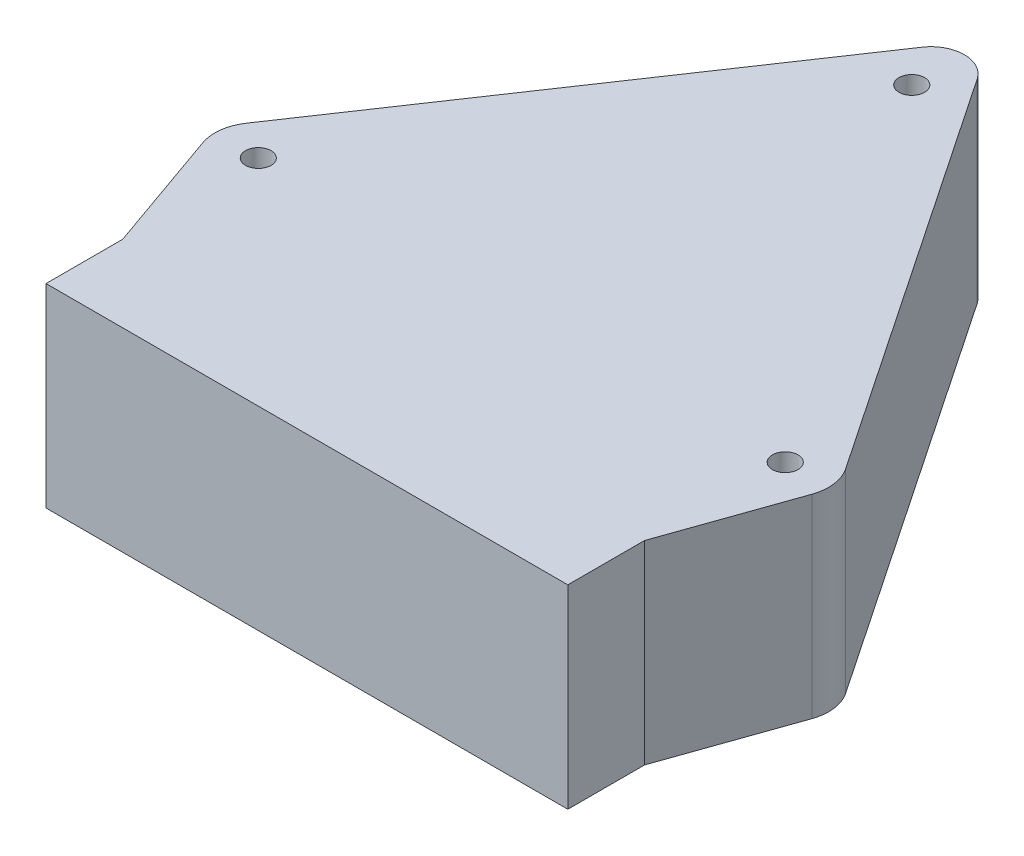
SolidWorks part; units mm, degrees
ref_plane "Front Plane" through (0, 0, 0) normal (0, 0, 1) x (1, 0, 0)
ref_plane "Top Plane" through (0, 0, 0) normal (0, 1, 0) x (1, 0, 0)
ref_plane "Right Plane" through (0, 0, 0) normal (1, 0, 0) x (0, 0, -1)
sketch "Front" plane through (0, 0, 0) normal (0, 0, 1) x (1, 0, 0)
  line L0 (0, 0) -> (0, 50000) construction
  line L1 (0, 0) -> (50000, 0) construction
sketch "Top" plane through (0, 0, 0) normal (0, 1, 0) x (1, 0, 0)
  line L0 (0, 0) -> (0, 28151.3067) construction
  line L1 (0, 0) -> (28151.3067, 0) construction
  line L2 (-38.1291, -33.2348) -> (28113.1775, -33.2348) construction
  line L3 (50.6436, -31.9672) -> (-15673.9721, 23244.9935) construction
  line L4 (-11.6211, 25.7974) -> (-15707.6673, -23208.8722) construction
  line L7 (-5.3903, 50.3977) -> (-58.5488, -28.4847)
  line L8 (-59.517, -36.0592) -> (-51, -60.2348)
  line L9 (-51, -60.2348) -> (-51, -75.2348)
  line L10 (-51, -75.2348) -> (51, -75.2348)
  line L11 (5.3903, 50.3977) -> (58.5488, -28.4847)
  line L12 (59.517, -36.0592) -> (51, -60.2348)
  line L13 (51, -60.2348) -> (51, -75.2348)
  circle A0 centre (-51.5, -33.2348) radius 4 construction
  circle A1 centre (51.5, -33.2348) radius 4 construction
  circle A2 centre (0, 43) radius 4 construction
  circle A3 centre (0, 0) radius 32.5 construction
  arc A4 (-58.5488, -28.4847) -> (-59.517, -36.0592) centre (-51.5, -33.2348) ccw
  arc A5 (-5.3903, 50.3977) -> (0, 53.2652) centre (0, 46.7652) cw
  arc A6 (5.3903, 50.3977) -> (0, 53.2652) centre (0, 46.7652) ccw
  arc A7 (58.5488, -28.4847) -> (59.517, -36.0592) centre (51.5, -33.2348) cw
  circle A8 centre (0, 43) radius 6.5 construction
  point P11 (0, 43)
  point P12 (51.5, -33.2348)
  point P15 (-51.5, -33.2348)
  point P45 (0, -75.2348)
  dimension "D3" = 111
  dimension "D4" = 95
  dimension "D5" = 8
  dimension "D6" = 102
  dimension "D7" = 100
  dimension "D9" = 65
  dimension "D10" = 84
  dimension "D12" = 120
  dimension "D15" = 13
  dimension "D1" = 103
  dimension "D8" = 76.2348
  dimension "D11" = 10.5
  dimension "D13" = 86.5
  dimension "D14" = 42
  dimension "D16" = 15
sketch "Right" plane through (0, 0, 0) normal (1, 0, 0) x (0, 0, -1)
  line L0 (0, 0) -> (0, 50000) construction
  line L1 (0, 0) -> (50000, 0) construction
extrude "Base Model" add sketch "Top" along normal mid plane 38
hole_wizard "Ø5.0 (5) Diameter Hole1" positions "Sketch2" profile "Sketch1" hole size "Ø5.0" standard "ISO" end condition through all
sketch "Sketch2" plane through (0, 19, 0) normal (0, 1, 0) x (1, 0, 0)
  point P0 (-51.5, -33.2348)
  point P3 (0, 43)
  point P6 (51.5, -33.2348)
sketch "Sketch1" plane through (-51.5, 19, 33.2348) normal (1, 0, 0) x (0, 0, 1)
  line L0 (0, 0) -> (0, 38)
  line L1 (0, 38) -> (2.5, 38)
  line L2 (2.5, 38) -> (2.5, 0)
  line L5 (2.5, 0) -> (0, 0)
  line L11 (0, -6.35) -> (0, 107.95) construction
  dimension "Thru Hole Dia." = 5
  dimension "Thru Hole Depth" = 38
